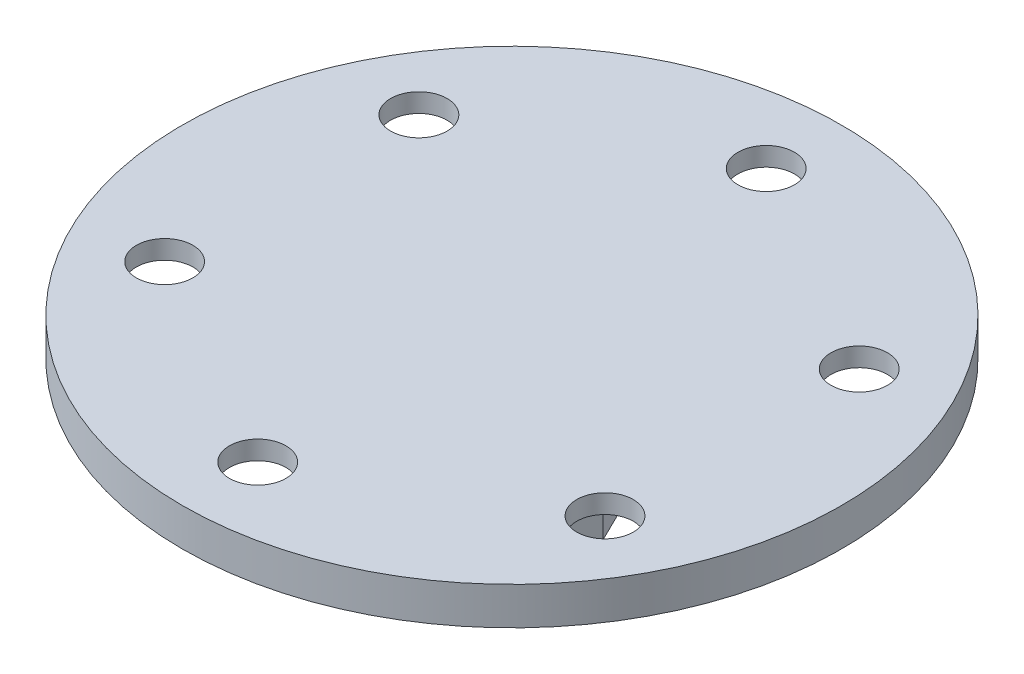
SolidWorks part; units mm, degrees
ref_plane "前视基准面" through (0, 0, 0) normal (0, 0, 1) x (1, 0, 0)
ref_plane "上视基准面" through (0, 0, 0) normal (0, 1, 0) x (1, 0, 0)
ref_plane "右视基准面" through (0, 0, 0) normal (1, 0, 0) x (0, 0, -1)
other "Configuration Table"
sketch "草图1" plane through (0, 0, 0) normal (0, 1, 0) x (1, 0, 0)
  circle A0 centre (0, 0) radius 17.5
  circle A1 centre (0, 0) radius 13.5 construction
  circle A2 centre (0, -13.5) radius 1.5
  circle A3 centre (-11.6913, -6.75) radius 1.5
  circle A4 centre (-11.6913, 6.75) radius 1.5
  circle A5 centre (0, 13.5) radius 1.5
  circle A6 centre (11.6913, 6.75) radius 1.5
  circle A7 centre (11.6913, -6.75) radius 1.5
  point P13 (0, 0)
  dimension "D1" = 35
  dimension "D2" = 27
  dimension "D3" = 3
  dimension "D4" = 6
extrude "凸台-拉伸1" add sketch "草图1" along normal blind 2
sketch "草图3" plane through (0, 2, 0) normal (0, 1, 0) x (1, 0, 0)
  circle A1 centre (0, 0) radius 17.5
  circle A2 centre (0, 0) radius 17.5
  dimension "D1" = 0
sketch "草图4" plane through (0, 0, 0) normal (0, -1, 0) x (1, 0, 0)
  line L0 (-0.4124, 2.9771) -> (-1.5001, 2.6044)
  line L9 (-2.1028, 2.0728) -> (-2.9268, 0.3897)
  line L10 (-2.9771, -0.4124) -> (-2.6044, -1.5001)
  line L11 (-2.0728, -2.1028) -> (-0.3897, -2.9268)
  line L12 (0.4124, -2.9771) -> (1.5001, -2.6044)
  line L13 (2.1028, -2.0728) -> (2.9268, -0.3897)
  line L14 (2.9771, 0.4124) -> (2.6044, 1.5001)
  line L15 (2.0728, 2.1028) -> (0.3897, 2.9268)
  line L48 (-0.3962, 2.9298) -> (-1.4839, 2.5571)
  line L49 (-2.0578, 2.0508) -> (-2.8819, 0.3677)
  line L50 (-2.9298, -0.3962) -> (-2.5571, -1.4839)
  line L51 (-2.0508, -2.0578) -> (-0.3677, -2.8819)
  line L52 (0.3962, -2.9298) -> (1.4839, -2.5571)
  line L53 (2.0578, -2.0508) -> (2.8819, -0.3677)
  line L54 (2.9298, 0.3962) -> (2.5571, 1.4839)
  line L55 (2.0508, 2.0578) -> (0.3677, 2.8819)
  line L56 (-0.3962, 2.9298) -> (-1.4839, 2.5571) construction
  line L57 (-2.0578, 2.0508) -> (-2.8819, 0.3677) construction
  line L58 (-2.9298, -0.3962) -> (-2.5571, -1.4839) construction
  line L59 (-2.0508, -2.0578) -> (-0.3677, -2.8819) construction
  line L60 (0.3962, -2.9298) -> (1.4839, -2.5571) construction
  line L61 (2.0578, -2.0508) -> (2.8819, -0.3677) construction
  line L62 (2.9298, 0.3962) -> (2.5571, 1.4839) construction
  line L63 (2.0508, 2.0578) -> (0.3677, 2.8819) construction
  line L128 (-2.9855, 3.681) -> (-4.7385, 0.1006)
  line L129 (-4.7385, 0.1006) -> (-3.681, -2.9855)
  line L130 (-3.681, -2.9855) -> (-0.1006, -4.7385)
  line L131 (-0.1006, -4.7385) -> (2.9855, -3.681)
  line L132 (2.9855, -3.681) -> (4.7385, -0.1006)
  line L133 (4.7385, -0.1006) -> (3.681, 2.9855)
  line L134 (3.681, 2.9855) -> (0.1006, 4.7385)
  line L135 (0.1006, 4.7385) -> (-2.9855, 3.681)
  arc A0 (-1.5001, 2.6044) -> (-2.1028, 2.0728) centre (-1.1597, 1.6111) ccw
  arc A1 (-2.9268, 0.3897) -> (-2.9771, -0.4124) centre (-1.9838, -0.072) ccw
  arc A2 (-2.6044, -1.5001) -> (-2.0728, -2.1028) centre (-1.6111, -1.1597) ccw
  arc A3 (-0.3897, -2.9268) -> (0.4124, -2.9771) centre (0.072, -1.9838) ccw
  arc A4 (1.5001, -2.6044) -> (2.1028, -2.0728) centre (1.1597, -1.6111) ccw
  arc A5 (2.9268, -0.3897) -> (2.9771, 0.4124) centre (1.9838, 0.072) ccw
  arc A6 (2.6044, 1.5001) -> (2.0728, 2.1028) centre (1.6111, 1.1597) ccw
  arc A7 (0.3897, 2.9268) -> (-0.4124, 2.9771) centre (-0.072, 1.9838) ccw
  arc A9 (-1.4839, 2.5571) -> (-2.0578, 2.0508) centre (-1.1597, 1.6111) ccw
  arc A10 (-2.8819, 0.3677) -> (-2.9298, -0.3962) centre (-1.9838, -0.072) ccw
  arc A11 (-2.5571, -1.4839) -> (-2.0508, -2.0578) centre (-1.6111, -1.1597) ccw
  arc A12 (-0.3677, -2.8819) -> (0.3962, -2.9298) centre (0.072, -1.9838) ccw
  arc A13 (1.4839, -2.5571) -> (2.0578, -2.0508) centre (1.1597, -1.6111) ccw
  arc A14 (2.8819, -0.3677) -> (2.9298, 0.3962) centre (1.9838, 0.072) ccw
  arc A15 (2.5571, 1.4839) -> (2.0508, 2.0578) centre (1.6111, 1.1597) ccw
  arc A16 (0.3677, 2.8819) -> (-0.3962, 2.9298) centre (-0.072, 1.9838) ccw
  arc A17 (-1.4839, 2.5571) -> (-2.0578, 2.0508) centre (-1.1597, 1.6111) ccw construction
  arc A18 (-2.8819, 0.3677) -> (-2.9298, -0.3962) centre (-1.9838, -0.072) ccw construction
  arc A19 (-2.5571, -1.4839) -> (-2.0508, -2.0578) centre (-1.6111, -1.1597) ccw construction
  arc A20 (-0.3677, -2.8819) -> (0.3962, -2.9298) centre (0.072, -1.9838) ccw construction
  arc A21 (1.4839, -2.5571) -> (2.0578, -2.0508) centre (1.1597, -1.6111) ccw construction
  arc A22 (2.8819, -0.3677) -> (2.9298, 0.3962) centre (1.9838, 0.072) ccw construction
  arc A23 (2.5571, 1.4839) -> (2.0508, 2.0578) centre (1.6111, 1.1597) ccw construction
  arc A24 (0.3677, 2.8819) -> (-0.3962, 2.9298) centre (-0.072, 1.9838) ccw construction
  dimension "D1" = 0
  dimension "D2" = 0.05
  dimension "D3" = 1.5
  dimension "D4" = 1.5
  dimension "D5" = 1.5
  dimension "D6" = 1.5
  dimension "D7" = 1.5
  dimension "D8" = 1.5
  dimension "D9" = 1.5
  dimension "D10" = 1.5
extrude "凸台-拉伸2" add sketch "草图4" along normal blind 6
sketch "草图5" plane through (0, 0, 0) normal (0, -1, 0) x (1, 0, 0)
  circle A0 centre (-11.6913, 6.75) radius 3
  circle A1 centre (0, 0) radius 13.5 construction
  circle A2 centre (0, 13.5) radius 3
  circle A3 centre (11.6913, 6.75) radius 3
  circle A4 centre (11.6913, -6.75) radius 3
  circle A5 centre (0, -13.5) radius 3
  circle A6 centre (-11.6913, -6.75) radius 3
  point P18 (0, 0)
  dimension "D1" = 6
  dimension "D2" = 6
extrude "切除-拉伸1" cut sketch "草图5" against normal blind 1
